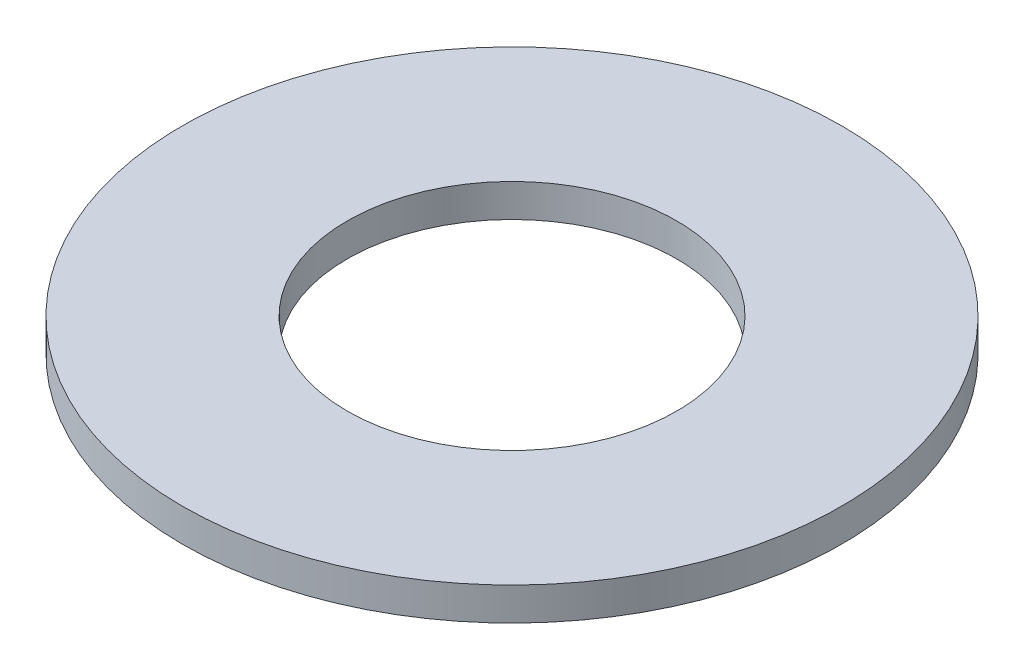
SolidWorks part; units mm, degrees
ref_plane "Front Plane" through (0, 0, 0) normal (0, 0, 1) x (1, 0, 0)
ref_plane "Top Plane" through (0, 0, 0) normal (0, 1, 0) x (1, 0, 0)
ref_plane "Right Plane" through (0, 0, 0) normal (1, 0, 0) x (0, 0, -1)
sketch "Sketch1" plane through (0, 0, 0) normal (0, 1, 0) x (1, 0, 0)
  circle A0 centre (0, 0) radius 12.7
  circle A1 centre (0, 0) radius 25.4
  dimension "D1" = 50.8
  dimension "D2" = 25.4
extrude "Boss-Extrude1" add sketch "Sketch1" along normal blind 2.54
